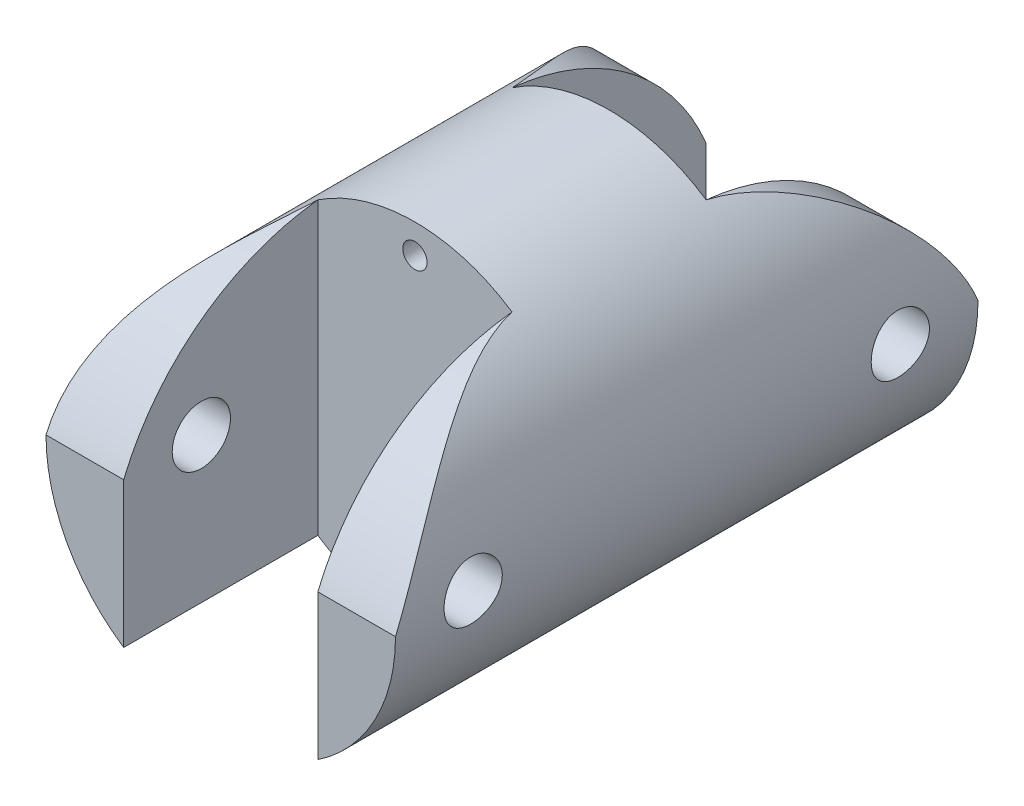
SolidWorks part; units mm, degrees
ref_plane "Front Plane" through (0, 0, 0) normal (0, 0, 1) x (1, 0, 0)
ref_plane "Top Plane" through (0, 0, 0) normal (0, 1, 0) x (1, 0, 0)
ref_plane "Right Plane" through (0, 0, 0) normal (1, 0, 0) x (0, 0, -1)
sketch "Sketch1" plane through (0, 0, 0) normal (0, 0, 1) x (1, 0, 0)
  circle A0 centre (0, 0) radius 9
extrude "Boss-Extrude1" add sketch "Sketch1" against normal blind 30
sketch "Sketch2" plane through (0, 0, 0) normal (0, 1, 0) x (1, 0, 0)
  line L0 (0, 20) -> (0, 0) construction
  line L1 (9, 30) -> (-9, 30) construction
  line L2 (-9, 15) -> (9, 15) construction
  line L3 (-9, 30) -> (-9, 0) construction
  line L4 (9, 0) -> (9, 30) construction
  line L5 (5, 30) -> (5, 20)
  line L6 (5, 30) -> (-5, 30)
  line L8 (5, 20) -> (-5, 20)
  line L9 (-5, 30) -> (-5, 20)
extrude "Cut-Extrude1" cut sketch "Sketch2" against normal through all both and the other way through all
sketch "Sketch4" plane through (0, 0, 0) normal (1, 0, 0) x (0, 0, -1)
  line L0 (20, 7.4833) -> (20, -7.4833) construction
  circle A1 centre (26, 0) radius 1.5
sketch "Sketch5" plane through (0, 0, 0) normal (1, 0, 0) x (0, 0, -1)
  line L0 (30, -7.4833) -> (30, 7.4833) construction
  line L1 (20, 7.4833) -> (30, 7.4833)
  line L2 (30, 7.4833) -> (30, 0)
  arc A0 (20, 7.4833) -> (30, 0) centre (18.7287, -4.6387) cw
extrude "Cut-Extrude3" cut sketch "Sketch5" against normal through all both and the other way through all
extrude "Cut-Extrude4" cut sketch "Sketch4" against normal blind 8 and the other way through all
ref_plane "Plane1" through (0, 0, -15) normal (0, 0, 1) x (1, 0, 0)
mirror "Mirror1" about plane through (0, 0, -15) normal (0, 0, 1) of "Cut-Extrude4", "Cut-Extrude3", "Cut-Extrude1"
sketch "Sketch6" plane through (0, 0, -10) normal (0, 0, 1) x (1, 0, 0)
  circle A0 centre (0, 7.5) radius 0.625
  dimension "D1" = 1.25
extrude "Cut-Extrude5" cut sketch "Sketch6" against normal blind 10
sketch "Sketch7" plane through (0, 0, -10) normal (0, 0, 1) x (1, 0, 0)
  line L1 (-1.5, -10) -> (1.5, -10)
  line L2 (-1.5, -10) -> (-1.5, -8)
  line L3 (-1.5, -8) -> (1.5, -8)
  line L4 (1.5, -10) -> (1.5, -8)
  line L5 (-1.5, -10) -> (1.5, -8) construction
  line L6 (-1.5, -8) -> (1.5, -10) construction
  arc A0 (-5, -7.4833) -> (5, -7.4833) centre (0, 0) ccw construction
  point P0 (0, -9)
  dimension "D1" = 2
  dimension "D2" = 3
extrude "Cut-Extrude6" cut sketch "Sketch7" against normal up to next
sketch "Sketch8" plane through (0, -8, 0) normal (0, -1, 0) x (1, 0, 0)
  circle A0 centre (0, -15) radius 0.9
extrude "Cut-Extrude7" cut sketch "Sketch8" against normal blind 5
